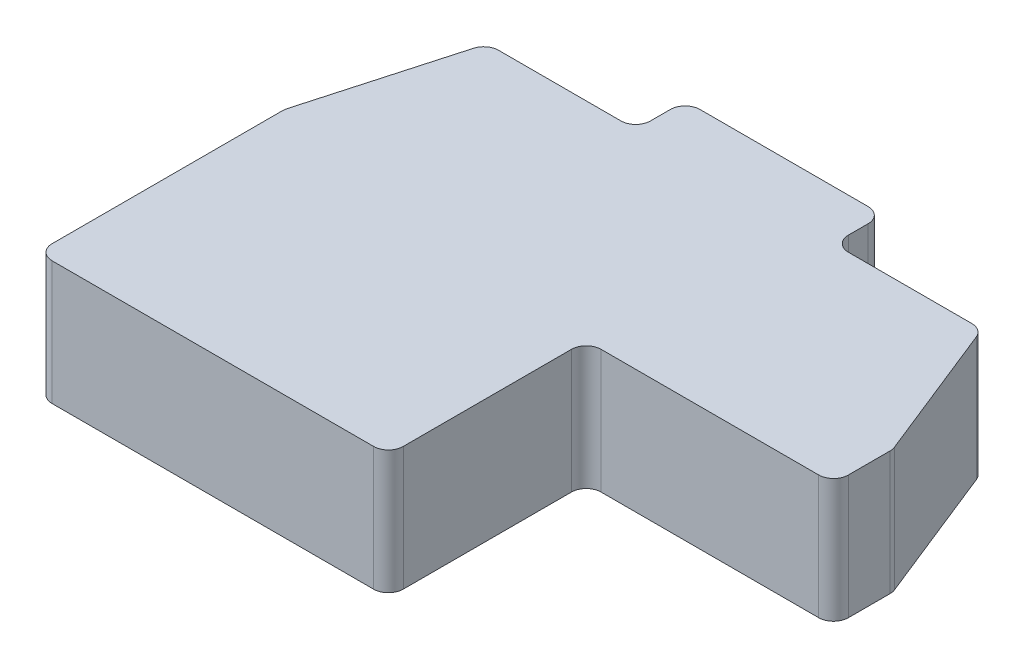
SolidWorks part; units mm, degrees
ref_plane "前视基准面" through (0, 0, 0) normal (0, 0, 1) x (1, 0, 0)
ref_plane "上视基准面" through (0, 0, 0) normal (0, 1, 0) x (1, 0, 0)
ref_plane "右视基准面" through (0, 0, 0) normal (1, 0, 0) x (0, 0, -1)
other "Configuration Table"
sketch "草图1" plane through (0, 0, 0) normal (0, 1, 0) x (1, 0, 0)
  line L0 (0, -3) -> (0, -37)
  line L1 (-3, -40) -> (-68, -40)
  line L2 (-71, -37) -> (-71, 9.5862)
  line L3 (3, 0) -> (47, 0)
  line L4 (50, 3) -> (50, 11.4223)
  line L7 (38.7543, 40.1142) -> (49.7854, 12.5364)
  line L8 (35.9689, 42) -> (11, 42)
  line L9 (8, 45) -> (8, 49)
  line L10 (5, 52) -> (-29, 52)
  line L11 (-32, 49) -> (-32, 45)
  line L12 (-35, 42) -> (-59.7274, 42)
  line L13 (-62.6153, 39.8122) -> (-70.888, 10.3984)
  arc A0 (8, 49) -> (5, 52) centre (5, 49) ccw
  arc A1 (11, 42) -> (8, 45) centre (11, 45) cw
  arc A2 (38.7543, 40.1142) -> (35.9689, 42) centre (35.9689, 39) ccw
  arc A3 (50, 11.4223) -> (49.7854, 12.5364) centre (47, 11.4223) ccw
  arc A4 (47, 0) -> (50, 3) centre (47, 3) ccw
  arc A5 (0, -3) -> (3, 0) centre (3, -3) cw
  arc A6 (0, -37) -> (-3, -40) centre (-3, -37) cw
  arc A7 (-68, -40) -> (-71, -37) centre (-68, -37) cw
  arc A8 (-71, 9.5862) -> (-70.888, 10.3984) centre (-68, 9.5862) cw
  arc A9 (-29, 52) -> (-32, 49) centre (-29, 49) ccw
  arc A10 (-32, 45) -> (-35, 42) centre (-35, 45) cw
  arc A11 (-59.7274, 42) -> (-62.6153, 39.8122) centre (-59.7274, 39) ccw
  point P25 (0, 0)
  dimension "D1" = 3
extrude "凸台-拉伸1" add sketch "草图1" along normal blind 25
